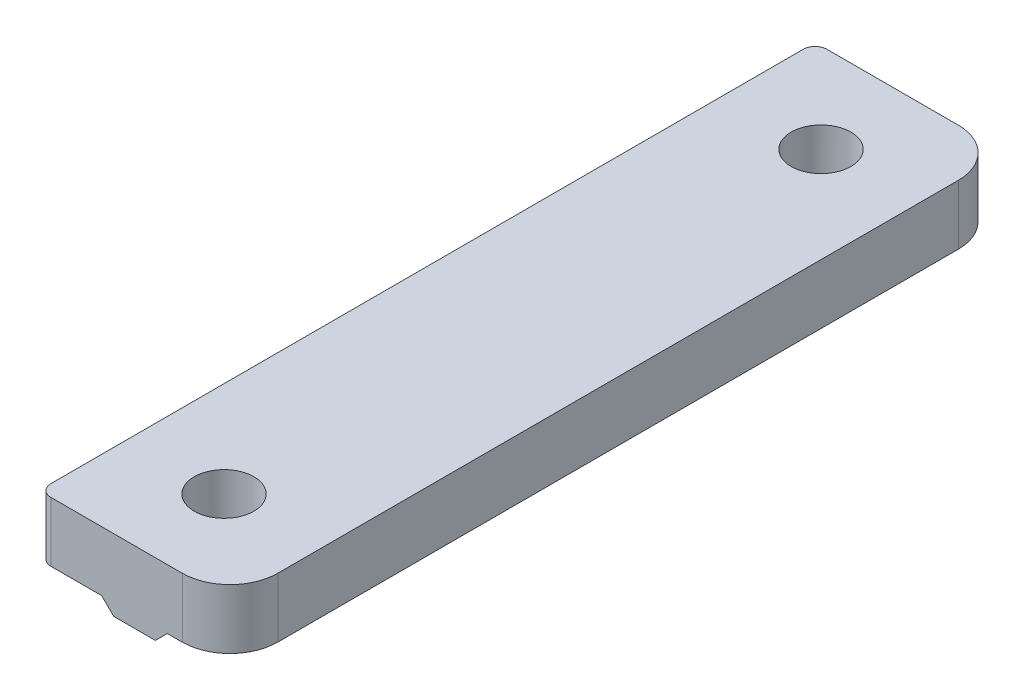
SolidWorks part; units mm, degrees
material "ABS"
ref_plane "Plan de face" through (0, 0, 0) normal (0, 0, 1) x (1, 0, 0)
ref_plane "Plan de dessus" through (0, 0, 0) normal (0, 1, 0) x (1, 0, 0)
ref_plane "Plan de droite" through (0, 0, 0) normal (1, 0, 0) x (0, 0, -1)
sketch "Esquisse1" plane through (0, 0, 0) normal (0, 0, 1) x (1, 0, 0)
  line L1 (-8, -2.5) -> (8, -2.5)
  line L2 (-8, -2.5) -> (-8, 2.5)
  line L3 (-8, 2.5) -> (8, 2.5)
  line L4 (8, -2.5) -> (8, 2.5)
  line L5 (-8, -2.5) -> (8, 2.5) construction
  line L6 (-8, 2.5) -> (8, -2.5) construction
  point P0 (0, 0)
  dimension "D1" = 16
  dimension "D2" = 5
extrude "Boss.-Extru.1" add sketch "Esquisse1" along normal blind 65
sketch "Esquisse4" plane through (0, 0, 65) normal (0, 0, 1) x (1, 0, 0)
  line L1 (-1.75, -3.5) -> (1.75, -3.5)
  line L2 (-1.75, -3.5) -> (-2.75, -2.5)
  line L3 (-2.75, -2.5) -> (2.75, -2.5)
  line L4 (1.75, -3.5) -> (2.75, -2.5)
  line L5 (-8, -2.5) -> (8, -2.5) construction
  point P5 (0, -2.5)
  point P10 (0, -3.5)
  dimension "D1" = 1
  dimension "D2" = 45
  dimension "D3" = 5.5
extrude "Boss.-Extru.3" add sketch "Esquisse4" against normal up to surface (65 mm away) up to face at (0, 0, 0)
sketch "Esquisse2" plane through (0, 2.5, 0) normal (0, 1, 0) x (1, 0, 0)
  line L0 (-8, -32.5) -> (8, -32.5) construction
  line L1 (-8, -65) -> (-8, 0) construction
  line L2 (8, -65) -> (8, 0) construction
  circle A0 centre (0, -7.5) radius 2.5
  circle A1 centre (0, -57.5) radius 2.5
  dimension "D1" = 5
  dimension "D2" = 50
extrude "Enlèv. mat.-Extru.1" cut sketch "Esquisse2" against normal through all
fillet "Congé1" radius 4 2 edges at (8, 0, 65) (8, 0, 0)
fillet "Congé2" radius 1 2 edges at (-8, 0, 0) (-8, 0, 65)
sketch "Esquisse3" plane through (0, 2.5, 0) normal (0, 1, 0) x (1, 0, 0)
  line L4 (4, 0) -> (-7, 0)
  line L5 (-8, -1) -> (-8, -64)
  line L6 (-7, -65) -> (4, -65)
  line L7 (8, -61) -> (8, -4)
  line L8 (4, 0) -> (-7, 0)
  line L9 (-8, -1) -> (-8, -64)
  line L10 (-7, -65) -> (4, -65)
  line L11 (8, -61) -> (8, -4)
  arc A4 (-7, 0) -> (-8, -1) centre (-7, -1) ccw
  arc A5 (-7, 0) -> (-8, -1) centre (-7, -1) ccw
  arc A6 (4, -65) -> (8, -61) centre (4, -61) ccw
  arc A7 (8, -4) -> (4, 0) centre (4, -4) ccw
  arc A10 (4, -65) -> (8, -61) centre (4, -61) ccw
  arc A11 (8, -4) -> (4, 0) centre (4, -4) ccw
  arc A12 (-8, -64) -> (-7, -65) centre (-7, -64) ccw
  arc A13 (-8, -64) -> (-7, -65) centre (-7, -64) ccw
  dimension "D1" = 0
extrude "Boss.-Extru.2" [suppressed] add sketch "Esquisse3" against normal blind 0.2
